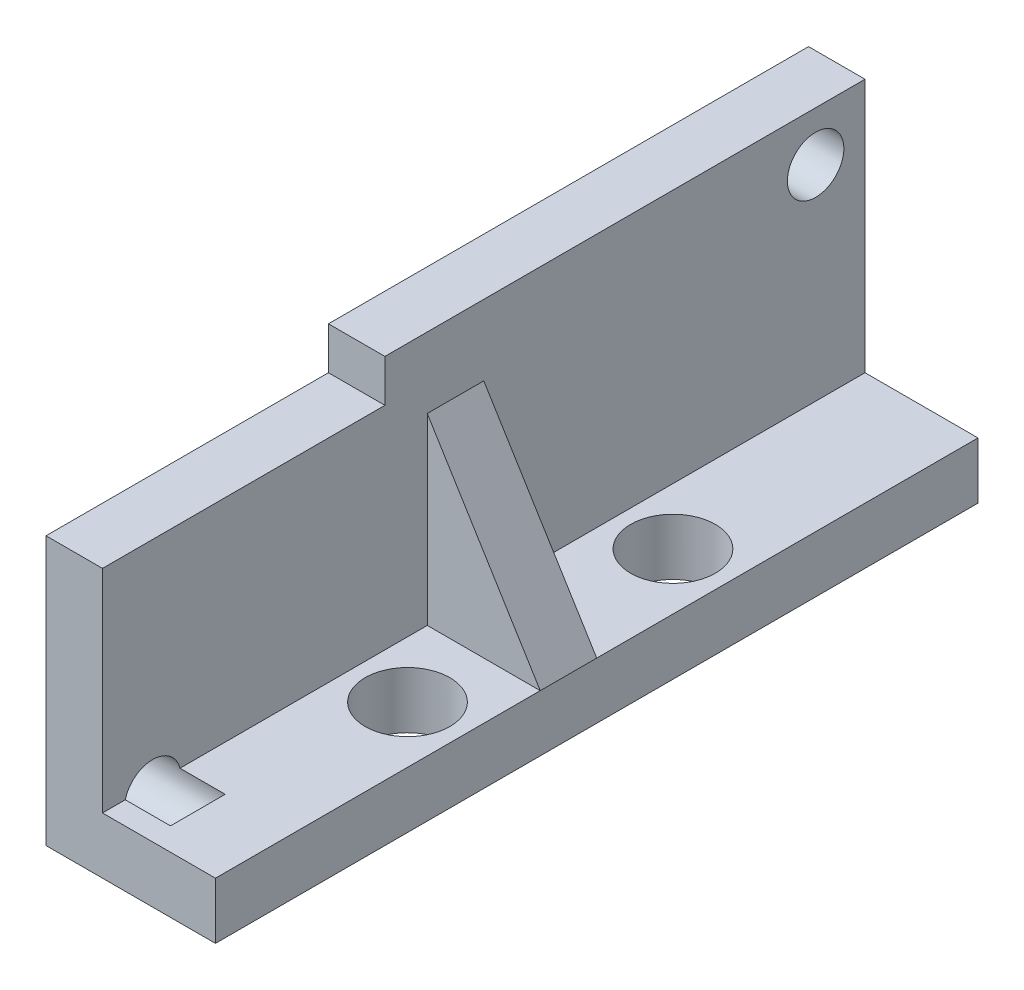
SolidWorks part; units mm, degrees
ref_plane "Front Plane" through (0, 0, 0) normal (0, 0, 1) x (1, 0, 0)
ref_plane "Top Plane" through (0, 0, 0) normal (0, 1, 0) x (1, 0, 0)
ref_plane "Right Plane" through (0, 0, 0) normal (1, 0, 0) x (0, 0, -1)
sketch "Sketch1" plane through (0, 0, 0) normal (0, 0, 1) x (1, 0, 0)
  line L0 (0, 11) -> (0, 0)
  line L1 (0, 0) -> (6, 0)
  line L2 (6, 0) -> (6, 2)
  line L3 (6, 2) -> (2, 2)
  line L4 (2, 2) -> (2, 11)
  line L5 (2, 11) -> (0, 11)
  dimension "D1" = 2
  dimension "D2" = 2
  dimension "D3" = 11
  dimension "D4" = 6
extrude "Boss-Extrude1" add sketch "Sketch1" along normal mid plane 27
sketch "Sketch2" plane through (2, 0, 0) normal (1, 0, 0) x (0, 0, -1)
  line L0 (-13.5, 11) -> (-13.5, 9.5)
  line L1 (-13.5, 2) -> (-13.5, 11) construction
  line L2 (-13.5, 9.5) -> (-3.5, 9.5)
  line L3 (-3.5, 9.5) -> (-3.5, 11)
  line L4 (-13.5, 11) -> (13.5, 11) construction
  line L5 (-13.5, 11) -> (-3.5, 11)
  dimension "D1" = 1.5
  dimension "D2" = 10
extrude "Cut-Extrude1" cut sketch "Sketch2" against normal blind 27
sketch "Sketch3" plane through (0, 0, 0) normal (-1, 0, 0) x (0, 0, 1)
  line L0 (13.5, 0) -> (-13.5, 0) construction
  line L2 (13.5, 9.5) -> (13.5, 0) construction
  circle A0 centre (-11.75, 9.25) radius 1
  circle A2 centre (11.7238, 1.75) radius 1
  dimension "D1" = 2
  dimension "D2" = 1.7762
  dimension "D3" = 1.75
extrude "Cut-Extrude2" cut sketch "Sketch3" against normal blind 3.6
sketch "Sketch4" plane through (0, 0, 13.5) normal (0, 0, 1) x (1, 0, 0)
  line L0 (0, 2) -> (6, 2)
  line L1 (0, 9.5) -> (0, 0) construction
  line L2 (6, 2) -> (6, 0)
  line L3 (6, 0) -> (0, 0)
  line L4 (0, 0) -> (0, 2)
extrude "Boss-Extrude2" add sketch "Sketch4" along normal blind 3
sketch "Sketch5" plane through (0, 2, 0) normal (0, 1, 0) x (1, 0, 0)
  line L0 (4, 13.5) -> (4, -16.5) construction
  line L1 (6, 13.5) -> (2, 13.5) construction
  line L2 (6, -16.5) -> (0, -16.5) construction
  line L3 (0, 0) -> (6, 0) construction
  line L4 (6, -16.5) -> (6, 13.5) construction
  line L5 (4, -13.5) -> (4, 16.5) construction
  circle A0 centre (4, 4.7) radius 1.5
  circle A2 centre (4, -4.7) radius 1.5
  dimension "D1" = 3
  dimension "D2" = 8.8
extrude "Cut-Extrude3" cut sketch "Sketch5" against normal blind 9
sketch "Sketch7" plane through (0, 0, 0) normal (0, 0, 1) x (1, 0, 0)
  line L0 (2, 8.5) -> (6, 2)
  line L1 (2, 2) -> (2, 9.5) construction
  line L2 (6, 2) -> (2, 2)
  line L3 (6, 2) -> (0, 2) construction
  line L4 (2, 2) -> (0, 2) construction
  line L5 (2, 2) -> (2, 8.5)
  dimension "D1" = 6.5
extrude "Boss-Extrude3" add sketch "Sketch7" along normal blind 2
sketch "Sketch8" plane through (0, 2, 0) normal (0, 1, 0) x (1, 0, 0)
  line L0 (0, -13.5) -> (6, -13.5)
  line L1 (6, -16.5) -> (6, -2) construction
  line L2 (6, -13.5) -> (6, -16.5)
  line L3 (6, -16.5) -> (0, -16.5)
  line L4 (0, -16.5) -> (0, -13.5)
  line L5 (6, -16.5) -> (0, -16.5) construction
extrude "Cut-Extrude4" cut sketch "Sketch8" against normal blind 10
